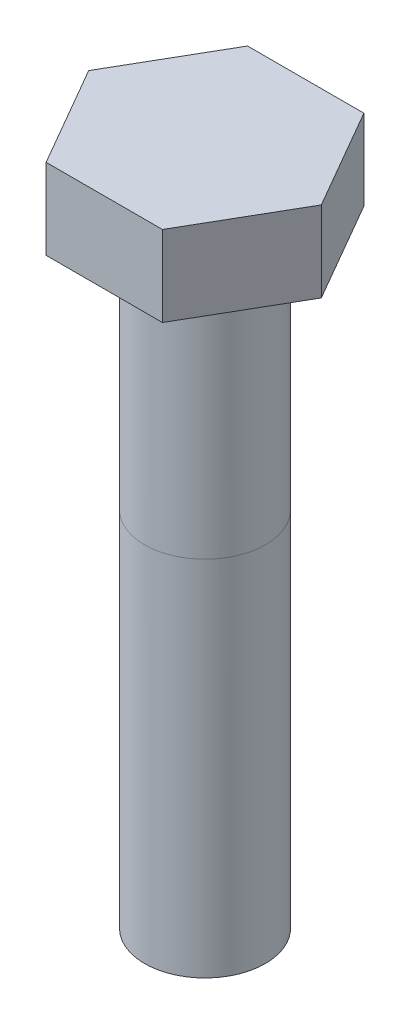
SolidWorks part; units mm, degrees
material "Простая углеродистая сталь"
ref_plane "спереди" through (0, 0, 0) normal (0, 0, 1) x (1, 0, 0)
ref_plane "сверху" through (0, 0, 0) normal (0, 1, 0) x (1, 0, 0)
ref_plane "справа" through (0, 0, 0) normal (1, 0, 0) x (0, 0, -1)
sketch "Эскиз1" plane through (0, 0, 0) normal (0, 1, 0) x (1, 0, 0)
  line L1 (5.7735, 0) -> (2.8868, 5)
  line L2 (2.8868, 5) -> (-2.8868, 5)
  line L3 (-2.8868, 5) -> (-5.7735, 0)
  line L4 (-5.7735, 0) -> (-2.8868, -5)
  line L5 (-2.8868, -5) -> (2.8868, -5)
  line L6 (2.8868, -5) -> (5.7735, 0)
  circle A0 centre (0, 0) radius 5 construction
  dimension "D1" = 10
extrude "Бобышка-Вытянуть1" add sketch "Эскиз1" along normal blind 4
sketch "Эскиз2" plane through (0, 0, 0) normal (0, -1, 0) x (1, 0, 0)
  circle A0 centre (0, 0) radius 3
  dimension "D1" = 6
extrude "Бобышка-Вытянуть2" add sketch "Эскиз2" along normal blind 30
sketch "Эскиз3" plane through (0, 0, 0) normal (0, 0, 1) x (1, 0, 0)
  line L0 (3, -12) -> (-3, -12)
  line L1 (0, 0) -> (0, -12) construction
  line L2 (3, -30) -> (3, 0) construction
  line L3 (-3, -30) -> (3, -30) construction
  point P3 (0, -12)
  dimension "D1" = 18
split line "Разделяющая линия1"
cosmetic thread "Условное изображение резьбы1" parameters "D1"=18, "D2"=4.891
equation "\"s\"= 10'размер под ключ"
equation "\"D1@Эскиз1\"=\"s\""
equation "\"k\"= 4'толщина головки"
equation "\"D1@Бобышка-Вытянуть1\" = \"k\""
equation "\"d\"= 6'номинальный диаметр резьбы"
equation "\"L\"= 30'*Длина [30; 200] шаг 5"
equation "\"D1@Бобышка-Вытянуть2\"=\"L\""
equation "\"D1@Эскиз2\"=\"d\""
equation "\"B\"= IIF ( \"L\" < = 125 , 18 , IIF ( \"L\" < = 200 , 24 , 24 ) )'длина резьбовой части"
equation "\"D1@Эскиз3\"=\"B\""
